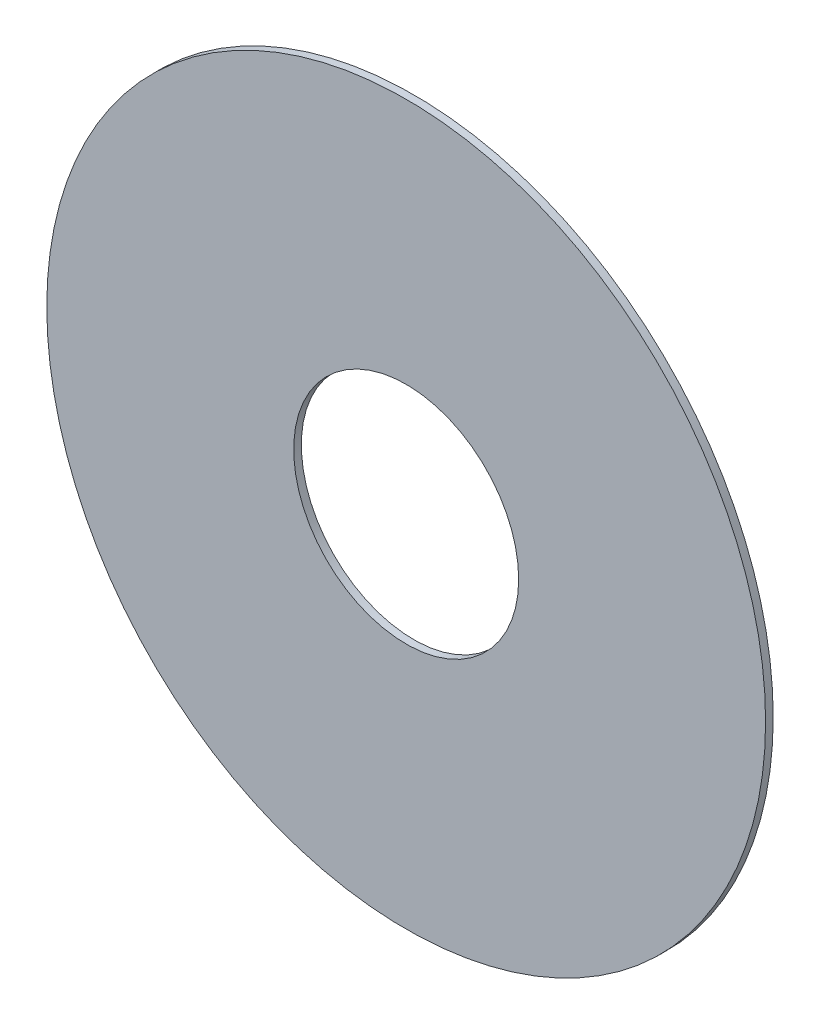
SolidWorks part; units mm, degrees
ref_plane "Спереди" through (0, 0, 0) normal (0, 0, 1) x (1, 0, 0)
ref_plane "Сверху" through (0, 0, 0) normal (0, 1, 0) x (1, 0, 0)
ref_plane "Справа" through (0, 0, 0) normal (1, 0, 0) x (0, 0, -1)
sketch "Эскиз1" plane through (0, 0, 0) normal (0, 0, 1) x (1, 0, 0)
  circle A0 centre (0, 0) radius 94.2462
  circle A1 centre (0, 0) radius 29.5
extrude "Printed_guard" add sketch "Эскиз1" along normal blind 2 from offset 45.5
